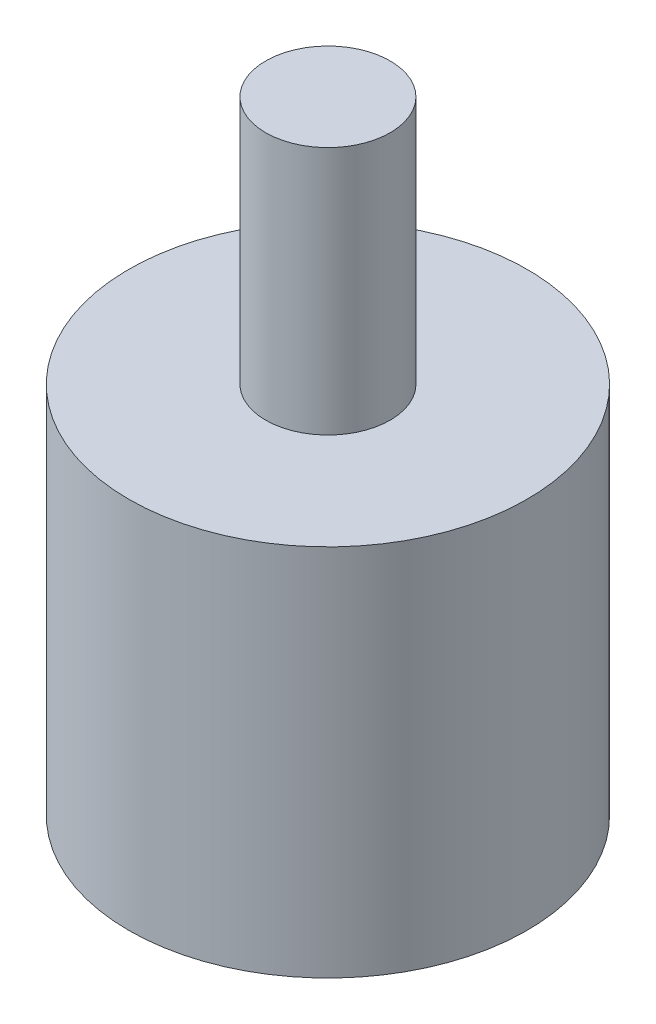
SolidWorks part; units mm, degrees
material "AISI 1020"
ref_plane "Alzado" through (0, 0, 0) normal (0, 0, 1) x (1, 0, 0)
ref_plane "Planta" through (0, 0, 0) normal (0, 1, 0) x (1, 0, 0)
ref_plane "Vista lateral" through (0, 0, 0) normal (1, 0, 0) x (0, 0, -1)
sketch "Croquis1" plane through (0, 0, 0) normal (0, 1, 0) x (1, 0, 0)
  circle A0 centre (0, 0) radius 8
  dimension "D1" = 16
extrude "Saliente-Extruir1" add sketch "Croquis1" along normal blind 15
sketch "Croquis2" plane through (0, 15, 0) normal (0, 1, 0) x (1, 0, 0)
  circle A0 centre (0, 0) radius 2.5
  dimension "D1" = 5
extrude "Saliente-Extruir2" add sketch "Croquis2" along normal blind 10
